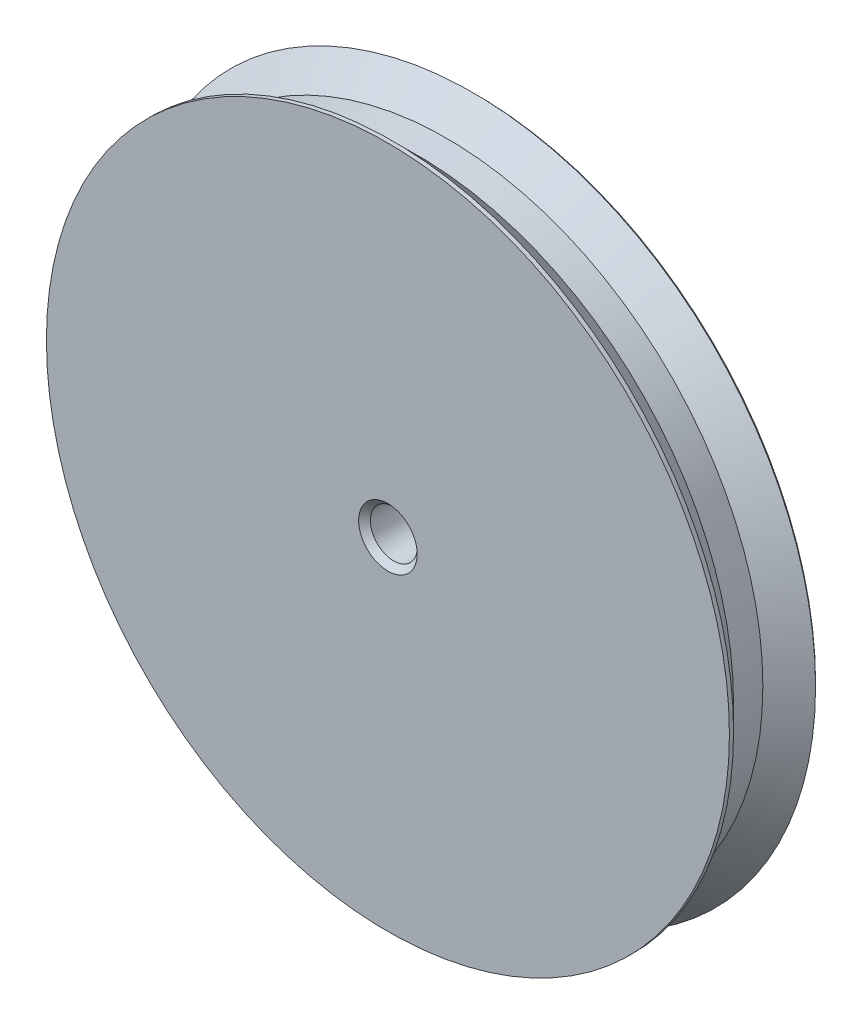
SolidWorks part; units mm, degrees
material "ABS"
ref_plane "Front Plane" through (0, 0, 0) normal (0, 0, 1) x (1, 0, 0)
ref_plane "Top Plane" through (0, 0, 0) normal (0, 1, 0) x (1, 0, 0)
ref_plane "Right Plane" through (0, 0, 0) normal (1, 0, 0) x (0, 0, -1)
sketch "Sketch1" plane through (0, 0, 0) normal (0, 1, 0) x (1, 0, 0)
  line L0 (59, 0) -> (54, 5)
  line L1 (4, 0) -> (59, 0)
  line L2 (4, 0) -> (4, 15)
  line L3 (4, 15) -> (59, 15)
  line L5 (54, 5) -> (54, 10)
  line L6 (54, 10) -> (59, 15)
  line L7 (0, 0) -> (0, 23.4305) construction
  point P5 (0, 23.4305)
  point P8 (4, 0)
  dimension "D1" = 15
  dimension "D2" = 50
  dimension "D3" = 55
  dimension "D4" = 55
  dimension "D5" = 5
  dimension "D6" = 5
  dimension "D7" = 4
revolve "Revolve1" add sketch "Sketch1" angle 360 about L7
chamfer "Chamfer1" distance 1 angle 45 4 edges at (59, 0, -15) (4, 0, -15) (4, 0, 0) (59, 0, 0)
